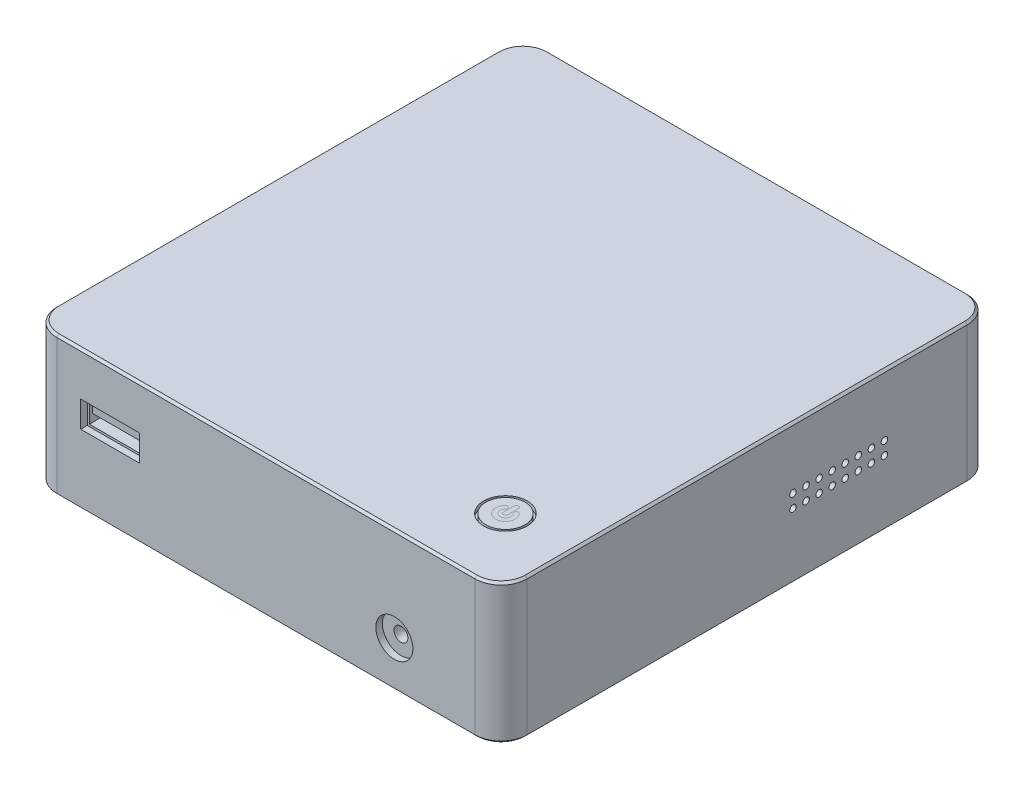
SolidWorks part; units mm, degrees
ref_plane "前视基准面" through (0, 0, 0) normal (0, 0, 1) x (1, 0, 0)
ref_plane "上视基准面" through (0, 0, 0) normal (0, 1, 0) x (1, 0, 0)
ref_plane "右视基准面" through (0, 0, 0) normal (1, 0, 0) x (0, 0, -1)
sketch "草图1" plane through (0, 0, 0) normal (0, 1, 0) x (1, 0, 0)
  line L1 (-48, -56.5) -> (48, -56.5)
  line L2 (-54, -50.5) -> (-54, 50.5)
  line L3 (-48, 56.5) -> (48, 56.5)
  line L4 (54, -50.5) -> (54, 50.5)
  line L5 (-54, -56.5) -> (54, 56.5) construction
  line L6 (-54, 56.5) -> (54, -56.5) construction
  arc A0 (-54, -50.5) -> (-48, -56.5) centre (-48, -50.5) ccw
  arc A1 (48, -56.5) -> (54, -50.5) centre (48, -50.5) ccw
  arc A2 (48, 56.5) -> (54, 50.5) centre (48, 50.5) cw
  arc A3 (-54, 50.5) -> (-48, 56.5) centre (-48, 50.5) cw
  point P0 (0, 0)
  dimension "D3" = 6
  dimension "D1" = 113
  dimension "D2" = 108
extrude "凸台-拉伸1" add sketch "草图1" along normal blind 32
sketch "草图2" plane through (0, 32, 0) normal (0, 1, 0) x (1, 0, 0)
  line L0 (54, -50.5) -> (54, 50.5) construction
  line L1 (-48, -56.5) -> (48, -56.5) construction
  circle A0 centre (39, -40.5) radius 5
  circle A1 centre (39, -40.5) radius 4.5
  dimension "D1" = 15
  dimension "D2" = 10
  dimension "D3" = 16
  dimension "D4" = 0.5
extrude "切除-拉伸1" cut sketch "草图2" against normal blind 1
sketch "草图3" plane through (0, 32, 0) normal (0, 1, 0) x (1, 0, 0)
  line L0 (39, -38) -> (39, -40.5) construction
  line L1 (39.5, -38) -> (39.5, -40.5)
  line L2 (38.5, -38) -> (38.5, -40.5)
  line L3 (39, -40.5) -> (39, -42.25) construction
  arc A0 (39.5, -38) -> (38.5, -38) centre (39, -38) ccw
  arc A1 (38.5, -40.5) -> (39.5, -40.5) centre (39, -40.5) ccw
  arc A2 (37.7626, -39.2626) -> (40.2374, -39.2626) centre (39, -40.5) ccw construction
  arc A3 (37.409, -38.909) -> (40.591, -38.909) centre (39, -40.5) ccw
  arc A4 (38.1161, -39.6161) -> (39.8839, -39.6161) centre (39, -40.5) ccw
  arc A5 (38.1161, -39.6161) -> (37.409, -38.909) centre (37.7626, -39.2626) ccw
  arc A6 (40.591, -38.909) -> (39.8839, -39.6161) centre (40.2374, -39.2626) ccw
  point P2 (39, -39.25)
  point P11 (39, -42.25)
  point P16 (39, -40.5)
  point P17 (40.4505, -39.521)
  dimension "D1" = 0.5
  dimension "D2" = 0.5
  dimension "D3" = 1.75
  dimension "D4" = 2.5
  dimension "D5" = 90
split line "分割线1"
sketch "草图4" plane through (54, 0, 0) normal (1, 0, 0) x (0, 0, -1)
  line L0 (56.5, 32) -> (56.5, 0) construction
  line L1 (-50.5, 0) -> (50.5, 0) construction
  circle A0 centre (10.5, 18) radius 0.75
  circle A1 centre (13.5, 18) radius 0.75
  circle A2 centre (16.5, 18) radius 0.75
  circle A3 centre (19.5, 18) radius 0.75
  circle A4 centre (22.5, 18) radius 0.75
  circle A5 centre (25.5, 18) radius 0.75
  circle A6 centre (28.5, 18) radius 0.75
  circle A7 centre (31.5, 18) radius 0.75
  circle A8 centre (13.5, 15) radius 0.75
  circle A9 centre (16.5, 15) radius 0.75
  circle A10 centre (19.5, 15) radius 0.75
  circle A11 centre (22.5, 15) radius 0.75
  circle A12 centre (25.5, 15) radius 0.75
  circle A13 centre (28.5, 15) radius 0.75
  circle A14 centre (31.5, 15) radius 0.75
  circle A15 centre (10.5, 15) radius 0.75
  point P2 (-8.9295, 21.1833)
  point P4 (0, 0)
  point P34 (0, 0)
  point P35 (3.3735, 19.2577)
  dimension "D4" = 1.5
  dimension "D5" = 3
  dimension "D6" = 25
  dimension "D7" = 15
  dimension "D3" = 3
  dimension "D1" = 8
  dimension "D2" = 2
extrude "切除-拉伸2" cut sketch "草图4" against normal blind 3
sketch "草图5" plane through (0, 0, 56.5) normal (0, 0, 1) x (1, 0, 0)
  line L0 (-48, 0) -> (48, 0) construction
  line L1 (-42.5, 22) -> (-29, 22)
  line L2 (-42.5, 22) -> (-42.5, 16)
  line L3 (-42.5, 16) -> (-29, 16)
  line L4 (-29, 22) -> (-29, 16)
  line L5 (54, 32) -> (54, 0) construction
  line L6 (-48, 32) -> (48, 32) construction
  line L7 (-54, 32) -> (-54, 0) construction
  circle A0 centre (29.5, 10.5) radius 4.25
  dimension "D1" = 8.5
  dimension "D2" = 10.5
  dimension "D3" = 24.5
  dimension "D4" = 13.5
  dimension "D5" = 6
  dimension "D6" = 10
  dimension "D7" = 11.5
extrude "切除-拉伸3" cut sketch "草图5" against normal blind 1.5
sketch "草图6" plane through (0, 0, 55) normal (0, 0, 1) x (1, 0, 0)
  line L0 (-29, 16) -> (-29, 22) construction
  line L1 (-42, 21.5) -> (-29.5, 21.5)
  line L2 (-42, 21.5) -> (-42, 16.5)
  line L3 (-42, 16.5) -> (-29.5, 16.5)
  line L4 (-29.5, 21.5) -> (-29.5, 16.5)
  line L5 (-41.25, 21) -> (-30.25, 21)
  line L6 (-41.25, 21) -> (-41.25, 19)
  line L7 (-41.25, 19) -> (-30.25, 19)
  line L8 (-30.25, 21) -> (-30.25, 19)
  line L9 (-29, 22) -> (-42.5, 22) construction
  circle A0 centre (29.5, 10.5) radius 1.6
  point P11 (-29.5, 19)
  point P14 (-29, 19)
  point P15 (-35.75, 21.5)
  point P18 (-35.75, 22)
  point P19 (-35.75, 21)
  dimension "D1" = 3.2
  dimension "D2" = 5
  dimension "D3" = 12.5
  dimension "D4" = 11
  dimension "D5" = 2
  dimension "D6" = 0.5
extrude "切除-拉伸4" cut sketch "草图6" against normal blind 10
sketch "草图7" plane through (-54, 0, 0) normal (-1, 0, 0) x (0, 0, 1)
  line L0 (56.5, 32) -> (56.5, 0) construction
  line L1 (-3.5, 22) -> (10, 22)
  line L2 (-3.5, 22) -> (-3.5, 16)
  line L3 (-3.5, 16) -> (10, 16)
  line L4 (10, 22) -> (10, 16)
  line L5 (19, 22) -> (32.5, 22)
  line L6 (19, 22) -> (19, 16)
  line L7 (19, 16) -> (32.5, 16)
  line L8 (32.5, 22) -> (32.5, 16)
  line L9 (-50.5, 32) -> (50.5, 32) construction
  dimension "D1" = 6
  dimension "D2" = 13.5
  dimension "D3" = 9
  dimension "D4" = 24
  dimension "D5" = 10
extrude "切除-拉伸5" cut sketch "草图7" against normal blind 1.5
sketch "草图8" plane through (-52.5, 0, 0) normal (-1, 0, 0) x (0, 0, 1)
  line L0 (10, 22) -> (-3.5, 22) construction
  line L5 (-2.25, 21) -> (8.75, 21)
  line L6 (-2.25, 21) -> (-2.25, 19)
  line L7 (-2.25, 19) -> (8.75, 19)
  line L8 (8.75, 21) -> (8.75, 19)
  line L13 (20.25, 21) -> (31.25, 21)
  line L14 (20.25, 21) -> (20.25, 19)
  line L15 (20.25, 19) -> (31.25, 19)
  line L16 (31.25, 21) -> (31.25, 19)
  line L23 (9.5, 16.5) -> (9.5, 21.5)
  line L24 (-3, 16.5) -> (9.5, 16.5)
  line L25 (-3, 21.5) -> (-3, 16.5)
  line L26 (9.5, 21.5) -> (-3, 21.5)
  line L27 (9.5, 16.5) -> (9.5, 21.5)
  line L28 (-3, 16.5) -> (9.5, 16.5)
  line L29 (-3, 21.5) -> (-3, 16.5)
  line L30 (9.5, 21.5) -> (-3, 21.5)
  line L41 (19.5, 16.5) -> (32, 16.5)
  line L42 (32, 16.5) -> (32, 21.5)
  line L43 (32, 21.5) -> (19.5, 21.5)
  line L44 (19.5, 21.5) -> (19.5, 16.5)
  line L45 (19.5, 16.5) -> (32, 16.5)
  line L46 (32, 16.5) -> (32, 21.5)
  line L47 (32, 21.5) -> (19.5, 21.5)
  line L48 (19.5, 21.5) -> (19.5, 16.5)
  point P0 (25.75, 21)
  point P1 (25.75, 21.5)
  point P18 (3.25, 22)
  point P19 (3.25, 21)
  dimension "D1" = 0.5
  dimension "D3" = 2
  dimension "D4" = 11
  dimension "D5" = 0.5
  dimension "D2" = 0.5
extrude "切除-拉伸6" cut sketch "草图8" against normal blind 10
sketch "草图9" plane through (0, 0, -56.5) normal (0, 0, -1) x (-1, 0, 0)
  line L0 (-27.5, 7) -> (-14.5, 7)
  line L1 (-44.8, 23) -> (-39.8, 23)
  line L2 (-45.8, 22) -> (-45.8, 21)
  line L3 (-44.8, 20) -> (-39.8, 20)
  line L4 (-38.8, 22) -> (-38.8, 21)
  line L5 (-36, 26.5) -> (-9.5, 26.5)
  line L6 (-37, 25.5) -> (-37, 18.7)
  line L7 (-36, 17.7) -> (-9.5, 17.7)
  line L8 (-8.5, 25.5) -> (-8.5, 18.7)
  line L9 (-5.5, 26.5) -> (21, 26.5)
  line L10 (-6.5, 25.5) -> (-6.5, 18.7)
  line L11 (-5.5, 17.7) -> (21, 17.7)
  line L12 (22, 25.5) -> (22, 18.7)
  line L13 (29, 21.7) -> (40.5, 21.7)
  line L14 (28, 20.7) -> (28, 10.2)
  line L15 (31, 7.2) -> (38.5, 7.2)
  line L16 (41.5, 20.7) -> (41.5, 10.2)
  line L17 (-13.5, 8) -> (-13.5, 9.5858)
  line L18 (-13.7929, 10.2929) -> (-15.7071, 12.2071)
  line L19 (-16.4142, 12.5) -> (-25.5858, 12.5)
  line L20 (-26.2929, 12.2071) -> (-28.2071, 10.2929)
  line L21 (-28.5, 9.5858) -> (-28.5, 8)
  line L22 (12.0429, 4.6071) -> (12.4571, 4.1929)
  line L23 (-5, 13.7) -> (1.5, 13.7)
  line L24 (-6, 12.7) -> (-6, 9.2)
  line L25 (-5, 8.2) -> (1.5, 8.2)
  line L26 (2.5, 12.7) -> (2.5, 9.2)
  line L27 (9.5, 14.7) -> (21, 14.7)
  line L28 (8.5, 13.7) -> (8.5, 5.9)
  line L29 (9.5, 4.9) -> (11.3358, 4.9)
  line L30 (22, 13.7) -> (22, 5.9)
  line L31 (13.1642, 3.9) -> (17.3358, 3.9)
  line L32 (18.0429, 4.1929) -> (18.4571, 4.6071)
  line L33 (-48, 0) -> (48, 0) construction
  line L34 (-54, 32) -> (-54, 0) construction
  line L35 (-48, 32) -> (48, 32) construction
  line L36 (54, 32) -> (54, 0) construction
  line L37 (19.1642, 4.9) -> (21, 4.9)
  line L38 (15.25, 3.9) -> (15.25, 14.7) construction
  circle A0 centre (-39, 9.5) radius 5
  arc A1 (28, 10.2) -> (31, 7.2) centre (31, 10.2) ccw
  arc A2 (38.5, 7.2) -> (41.5, 10.2) centre (38.5, 10.2) ccw
  arc A3 (1.5, 8.2) -> (2.5, 9.2) centre (1.5, 9.2) ccw
  arc A4 (1.5, 13.7) -> (2.5, 12.7) centre (1.5, 12.7) cw
  arc A5 (-5, 13.7) -> (-6, 12.7) centre (-5, 12.7) ccw
  arc A6 (-6, 9.2) -> (-5, 8.2) centre (-5, 9.2) ccw
  arc A7 (-27.5, 7) -> (-28.5, 8) centre (-27.5, 8) cw
  arc A8 (-14.5, 7) -> (-13.5, 8) centre (-14.5, 8) ccw
  arc A9 (-13.5, 9.5858) -> (-13.7929, 10.2929) centre (-14.5, 9.5858) ccw
  arc A10 (-15.7071, 12.2071) -> (-16.4142, 12.5) centre (-16.4142, 11.5) ccw
  arc A11 (-25.5858, 12.5) -> (-26.2929, 12.2071) centre (-25.5858, 11.5) ccw
  arc A12 (-28.2071, 10.2929) -> (-28.5, 9.5858) centre (-27.5, 9.5858) ccw
  arc A13 (-39.8, 20) -> (-38.8, 21) centre (-39.8, 21) ccw
  arc A14 (-39.8, 23) -> (-38.8, 22) centre (-39.8, 22) cw
  arc A15 (-45.8, 21) -> (-44.8, 20) centre (-44.8, 21) ccw
  arc A16 (-44.8, 23) -> (-45.8, 22) centre (-44.8, 22) ccw
  arc A17 (-37, 18.7) -> (-36, 17.7) centre (-36, 18.7) ccw
  arc A18 (-36, 26.5) -> (-37, 25.5) centre (-36, 25.5) ccw
  arc A19 (-9.5, 26.5) -> (-8.5, 25.5) centre (-9.5, 25.5) cw
  arc A20 (-9.5, 17.7) -> (-8.5, 18.7) centre (-9.5, 18.7) ccw
  arc A21 (-6.5, 18.7) -> (-5.5, 17.7) centre (-5.5, 18.7) ccw
  arc A22 (-5.5, 26.5) -> (-6.5, 25.5) centre (-5.5, 25.5) ccw
  arc A23 (21, 26.5) -> (22, 25.5) centre (21, 25.5) cw
  arc A24 (21, 17.7) -> (22, 18.7) centre (21, 18.7) ccw
  arc A25 (9.5, 14.7) -> (8.5, 13.7) centre (9.5, 13.7) ccw
  arc A26 (8.5, 5.9) -> (9.5, 4.9) centre (9.5, 5.9) ccw
  arc A27 (12.0429, 4.6071) -> (11.3358, 4.9) centre (11.3358, 3.9) ccw
  arc A28 (12.4571, 4.1929) -> (13.1642, 3.9) centre (13.1642, 4.9) ccw
  arc A29 (17.3358, 3.9) -> (18.0429, 4.1929) centre (17.3358, 4.9) ccw
  arc A30 (18.4571, 4.6071) -> (19.1642, 4.9) centre (19.1642, 3.9) cw
  arc A31 (21, 4.9) -> (22, 5.9) centre (21, 5.9) ccw
  arc A32 (21, 14.7) -> (22, 13.7) centre (21, 13.7) cw
  arc A33 (40.5, 21.7) -> (41.5, 20.7) centre (40.5, 20.7) cw
  arc A34 (29, 21.7) -> (28, 20.7) centre (29, 20.7) ccw
  point P40 (-21, 12.5)
  point P41 (-21, 7)
  point P49 (18.0875, 2.4436)
  point P50 (20.0821, 4.9)
  point P57 (2.5, 8.2)
  point P60 (2.5, 13.7)
  point P63 (-6, 13.7)
  point P68 (-28.5, 7)
  point P71 (-13.5, 7)
  point P74 (-13.5, 10)
  point P77 (-16, 12.5)
  point P84 (-38.8, 20)
  point P87 (-38.8, 23)
  point P92 (-45.8, 23)
  point P95 (-37, 17.7)
  point P98 (-37, 26.5)
  point P101 (-8.5, 26.5)
  point P114 (8.5, 14.7)
  point P119 (11.75, 4.9)
  point P126 (18.75, 4.9)
  point P129 (22, 4.9)
  point P132 (22, 14.7)
  point P135 (41.5, 21.7)
  point P138 (28, 21.7)
  dimension "D1" = 10
  dimension "D2" = 9.5
  dimension "D3" = 15
  dimension "D33" = 3
  dimension "D34" = 1
  dimension "D4" = 5.5
  dimension "D5" = 7
  dimension "D6" = 15
  dimension "D7" = 45
  dimension "D8" = 2.5
  dimension "D9" = 10.5
  dimension "D10" = 5.5
  dimension "D11" = 2
  dimension "D12" = 28.5
  dimension "D13" = 8.8
  dimension "D14" = 17
  dimension "D15" = 1.8
  dimension "D16" = 7
  dimension "D17" = 3
  dimension "D18" = 9
  dimension "D19" = 12.5
  dimension "D20" = 14.5
  dimension "D21" = 10.3
  dimension "D22" = 13.5
  dimension "D23" = 6
  dimension "D24" = 13.5
  dimension "D25" = 3
  dimension "D26" = 9.8
  dimension "D27" = 7
  dimension "D28" = 1
  dimension "D29" = 6
  dimension "D30" = 8.5
  dimension "D31" = 5.5
  dimension "D32" = 4
extrude "切除-拉伸7" cut sketch "草图9" against normal blind 1.5
sketch "草图10" plane through (0, 0, -55) normal (0, 0, -1) x (-1, 0, 0)
  line L4 (-38.8, 21) -> (-38.8, 22)
  line L5 (-39.8, 23) -> (-44.8, 23)
  line L6 (-45.8, 22) -> (-45.8, 21)
  line L7 (-44.8, 20) -> (-39.8, 20)
  line L8 (-38.8, 21) -> (-38.8, 22)
  line L9 (-39.8, 23) -> (-44.8, 23)
  line L10 (-45.8, 22) -> (-45.8, 21)
  line L11 (-44.8, 20) -> (-39.8, 20)
  line L20 (-27.5, 7.5) -> (-14.5, 7.5)
  line L21 (-14, 8) -> (-14, 9.5858)
  line L22 (-14.1464, 9.9393) -> (-16.0607, 11.8536)
  line L23 (-16.4142, 12) -> (-25.5858, 12)
  line L24 (-25.9393, 11.8536) -> (-27.8536, 9.9393)
  line L25 (-28, 9.5858) -> (-28, 8)
  line L26 (-27.5, 7.5) -> (-14.5, 7.5)
  line L27 (-14, 8) -> (-14, 9.5858)
  line L28 (-14.1464, 9.9393) -> (-16.0607, 11.8536)
  line L29 (-16.4142, 12) -> (-25.5858, 12)
  line L30 (-25.9393, 11.8536) -> (-27.8536, 9.9393)
  line L31 (-28, 9.5858) -> (-28, 8)
  line L34 (21, 14.7) -> (9.5, 14.7) construction
  line L35 (10, 14.2) -> (20.5, 14.2)
  line L36 (9.5, 13.7) -> (9.5, 6.7)
  line L37 (10, 6.2) -> (13.25, 6.2)
  line L38 (2, 9.2) -> (2, 12.7)
  line L39 (1.5, 13.2) -> (-5, 13.2)
  line L40 (-5.5, 12.7) -> (-5.5, 9.2)
  line L41 (-5, 8.7) -> (1.5, 8.7)
  line L42 (2, 9.2) -> (2, 12.7)
  line L43 (1.5, 13.2) -> (-5, 13.2)
  line L44 (-5.5, 12.7) -> (-5.5, 9.2)
  line L45 (-5, 8.7) -> (1.5, 8.7)
  line L46 (21, 13.7) -> (21, 6.7)
  line L47 (21, 14.7) -> (9.5, 14.7) construction
  line L48 (22, 5.9) -> (22, 13.7) construction
  line L49 (13.1642, 3.9) -> (17.3358, 3.9) construction
  line L50 (31.75, 11.7) -> (37.75, 11.7) construction
  line L51 (13.25, 6.2) -> (13.25, 3.9)
  line L52 (13.25, 3.9) -> (17.25, 3.9)
  line L53 (17.25, 6.2) -> (17.25, 3.9)
  line L54 (17.25, 6.2) -> (20.5, 6.2)
  line L55 (29, 20.7) -> (40.5, 20.7)
  line L56 (28.5, 20.2) -> (28.5, 16.2)
  line L57 (29, 15.7) -> (40.5, 15.7)
  line L58 (41, 20.2) -> (41, 16.2)
  line L59 (29.75, 20.2) -> (39.75, 20.2)
  line L60 (29.25, 19.7) -> (29.25, 18.7)
  line L61 (29.75, 18.2) -> (39.75, 18.2)
  line L62 (40.25, 19.7) -> (40.25, 18.7)
  line L63 (31.75, 13.2) -> (37.75, 13.2)
  line L64 (31.75, 10.2) -> (37.75, 10.2)
  line L65 (31.75, 11.7) -> (37.75, 11.7) construction
  line L66 (31.75, 11.95) -> (37.75, 11.95)
  line L67 (31.75, 11.45) -> (37.75, 11.45)
  line L68 (31, 7.2) -> (38.5, 7.2) construction
  line L69 (40.5, 21.7) -> (29, 21.7) construction
  line L71 (40.5, 21.7) -> (29, 21.7) construction
  line L72 (-25.5, 9.5858) -> (-16.5, 9.5858) construction
  line L73 (-25.5, 9.8358) -> (-16.5, 9.8358)
  line L74 (-25.5, 9.3358) -> (-16.5, 9.3358)
  line L76 (-5.25, 11.95) -> (1.75, 11.95)
  line L77 (-5.25, 11.95) -> (-5.25, 9.95)
  line L78 (-5.25, 9.95) -> (1.75, 9.95)
  line L79 (1.75, 11.95) -> (1.75, 9.95)
  circle A0 centre (-39, 9.5) radius 3.25
  circle A1 centre (-39, 9.5) radius 1.25
  arc A4 (-39.8, 20) -> (-38.8, 21) centre (-39.8, 21) ccw
  arc A5 (-38.8, 22) -> (-39.8, 23) centre (-39.8, 22) ccw
  arc A6 (-44.8, 23) -> (-45.8, 22) centre (-44.8, 22) ccw
  arc A7 (-45.8, 21) -> (-44.8, 20) centre (-44.8, 21) ccw
  arc A8 (-39.8, 20) -> (-38.8, 21) centre (-39.8, 21) ccw
  arc A9 (-38.8, 22) -> (-39.8, 23) centre (-39.8, 22) ccw
  arc A10 (-44.8, 23) -> (-45.8, 22) centre (-44.8, 22) ccw
  arc A11 (-45.8, 21) -> (-44.8, 20) centre (-44.8, 21) ccw
  arc A22 (-28, 8) -> (-27.5, 7.5) centre (-27.5, 8) ccw
  arc A23 (-14.5, 7.5) -> (-14, 8) centre (-14.5, 8) ccw
  arc A24 (-14, 9.5858) -> (-14.1464, 9.9393) centre (-14.5, 9.5858) ccw
  arc A25 (-16.0607, 11.8536) -> (-16.4142, 12) centre (-16.4142, 11.5) ccw
  arc A26 (-25.5858, 12) -> (-25.9393, 11.8536) centre (-25.5858, 11.5) ccw
  arc A27 (-27.8536, 9.9393) -> (-28, 9.5858) centre (-27.5, 9.5858) ccw
  arc A28 (-28, 8) -> (-27.5, 7.5) centre (-27.5, 8) ccw
  arc A29 (-14.5, 7.5) -> (-14, 8) centre (-14.5, 8) ccw
  arc A30 (-14, 9.5858) -> (-14.1464, 9.9393) centre (-14.5, 9.5858) ccw
  arc A31 (-16.0607, 11.8536) -> (-16.4142, 12) centre (-16.4142, 11.5) ccw
  arc A32 (-25.5858, 12) -> (-25.9393, 11.8536) centre (-25.5858, 11.5) ccw
  arc A33 (-27.8536, 9.9393) -> (-28, 9.5858) centre (-27.5, 9.5858) ccw
  arc A36 (31.75, 13.2) -> (31.75, 10.2) centre (31.75, 11.7) ccw
  arc A37 (37.75, 10.2) -> (37.75, 13.2) centre (37.75, 11.7) ccw
  arc A38 (31.75, 11.95) -> (31.75, 11.45) centre (31.75, 11.7) ccw
  arc A39 (37.75, 11.45) -> (37.75, 11.95) centre (37.75, 11.7) ccw
  arc A40 (1.5, 8.7) -> (2, 9.2) centre (1.5, 9.2) ccw
  arc A41 (2, 12.7) -> (1.5, 13.2) centre (1.5, 12.7) ccw
  arc A42 (-5, 13.2) -> (-5.5, 12.7) centre (-5, 12.7) ccw
  arc A43 (-5.5, 9.2) -> (-5, 8.7) centre (-5, 9.2) ccw
  arc A44 (1.5, 8.7) -> (2, 9.2) centre (1.5, 9.2) ccw
  arc A45 (2, 12.7) -> (1.5, 13.2) centre (1.5, 12.7) ccw
  arc A46 (-5, 13.2) -> (-5.5, 12.7) centre (-5, 12.7) ccw
  arc A47 (-5.5, 9.2) -> (-5, 8.7) centre (-5, 9.2) ccw
  arc A48 (10, 14.2) -> (9.5, 13.7) centre (10, 13.7) ccw
  arc A49 (9.5, 6.7) -> (10, 6.2) centre (10, 6.7) ccw
  arc A50 (20.5, 6.2) -> (21, 6.7) centre (20.5, 6.7) ccw
  arc A51 (20.5, 14.2) -> (21, 13.7) centre (20.5, 13.7) cw
  arc A52 (39.75, 20.2) -> (40.25, 19.7) centre (39.75, 19.7) cw
  arc A53 (39.75, 18.2) -> (40.25, 18.7) centre (39.75, 18.7) ccw
  arc A54 (29.25, 18.7) -> (29.75, 18.2) centre (29.75, 18.7) ccw
  arc A55 (29.75, 20.2) -> (29.25, 19.7) centre (29.75, 19.7) ccw
  arc A56 (29, 20.7) -> (28.5, 20.2) centre (29, 20.2) ccw
  arc A57 (28.5, 16.2) -> (29, 15.7) centre (29, 16.2) ccw
  arc A58 (40.5, 15.7) -> (41, 16.2) centre (40.5, 16.2) ccw
  arc A59 (40.5, 20.7) -> (41, 20.2) centre (40.5, 20.2) cw
  arc A60 (-25.5, 9.8358) -> (-25.5, 9.3358) centre (-25.5, 9.5858) ccw
  arc A61 (-16.5, 9.3358) -> (-16.5, 9.8358) centre (-16.5, 9.5858) ccw
  point P20 (15.25, 14.2)
  point P23 (15.25, 14.7)
  point P74 (34.75, 11.7)
  point P81 (34.75, 11.7)
  point P86 (-21, 9.5858)
  point P89 (34.75, 7.2)
  point P90 (34.75, 20.7)
  point P91 (34.75, 20.2)
  point P94 (34.75, 21.7)
  point P103 (21, 6.2)
  point P106 (21, 14.2)
  point P109 (40.25, 20.2)
  point P114 (29.25, 18.2)
  point P117 (29.25, 20.2)
  point P120 (28.5, 20.7)
  point P123 (28.5, 15.7)
  point P128 (41, 20.7)
  point P135 (-1.75, 11.95)
  point P136 (-21, 12)
  point P141 (-1.75, 13.2)
  point P142 (1.75, 10.95)
  point P143 (2, 10.95)
  dimension "D2" = 6.5
  dimension "D3" = 2.5
  dimension "D20" = 0.5
  dimension "D6" = 0.5
  dimension "D7" = 1
  dimension "D8" = 8
  dimension "D9" = 4
  dimension "D10" = 3
  dimension "D11" = 0.5
  dimension "D12" = 6
  dimension "D13" = 4.5
  dimension "D14" = 12.5
  dimension "D15" = 11
  dimension "D16" = 2
  dimension "D17" = 0.5
  dimension "D18" = 5
  dimension "D19" = 1
  dimension "D21" = 0.5
  dimension "D22" = 9
  dimension "D23" = 7
  dimension "D24" = 2
  dimension "D1" = 0
  dimension "D4" = 0.5
  dimension "D5" = 0.5
extrude "切除-拉伸8" cut sketch "草图10" against normal blind 10
sketch "草图11" plane through (0, 0, -55) normal (0, 0, -1) x (-1, 0, 0)
  line L0 (-36, 17.7) -> (-9.5, 17.7) construction
  line L1 (-36, 26.5) -> (-35, 26.5)
  line L2 (-36, 26.5) -> (-36, 17.7)
  line L3 (-36, 17.7) -> (-35, 17.7)
  line L4 (-35, 26.5) -> (-35, 17.7)
  line L5 (-34.0385, 26.5) -> (-33.0385, 26.5)
  line L6 (-34.0385, 26.5) -> (-34.0385, 17.7)
  line L7 (-34.0385, 17.7) -> (-33.0385, 17.7)
  line L8 (-33.0385, 26.5) -> (-33.0385, 17.7)
  line L9 (-32.0769, 26.5) -> (-31.0769, 26.5)
  line L10 (-32.0769, 26.5) -> (-32.0769, 17.7)
  line L11 (-32.0769, 17.7) -> (-31.0769, 17.7)
  line L12 (-31.0769, 26.5) -> (-31.0769, 17.7)
  line L13 (-30.1154, 26.5) -> (-29.1154, 26.5)
  line L14 (-30.1154, 26.5) -> (-30.1154, 17.7)
  line L15 (-30.1154, 17.7) -> (-29.1154, 17.7)
  line L16 (-29.1154, 26.5) -> (-29.1154, 17.7)
  line L17 (-28.1538, 26.5) -> (-27.1538, 26.5)
  line L18 (-28.1538, 26.5) -> (-28.1538, 17.7)
  line L19 (-28.1538, 17.7) -> (-27.1538, 17.7)
  line L20 (-27.1538, 26.5) -> (-27.1538, 17.7)
  line L21 (-26.1923, 26.5) -> (-25.1923, 26.5)
  line L22 (-26.1923, 26.5) -> (-26.1923, 17.7)
  line L23 (-26.1923, 17.7) -> (-25.1923, 17.7)
  line L24 (-25.1923, 26.5) -> (-25.1923, 17.7)
  line L25 (-24.2308, 26.5) -> (-23.2308, 26.5)
  line L26 (-24.2308, 26.5) -> (-24.2308, 17.7)
  line L27 (-24.2308, 17.7) -> (-23.2308, 17.7)
  line L28 (-23.2308, 26.5) -> (-23.2308, 17.7)
  line L29 (-22.2692, 26.5) -> (-21.2692, 26.5)
  line L30 (-22.2692, 26.5) -> (-22.2692, 17.7)
  line L31 (-22.2692, 17.7) -> (-21.2692, 17.7)
  line L32 (-21.2692, 26.5) -> (-21.2692, 17.7)
  line L33 (-20.3077, 26.5) -> (-19.3077, 26.5)
  line L34 (-20.3077, 26.5) -> (-20.3077, 17.7)
  line L35 (-20.3077, 17.7) -> (-19.3077, 17.7)
  line L36 (-19.3077, 26.5) -> (-19.3077, 17.7)
  line L37 (-18.3462, 26.5) -> (-17.3462, 26.5)
  line L38 (-18.3462, 26.5) -> (-18.3462, 17.7)
  line L39 (-18.3462, 17.7) -> (-17.3462, 17.7)
  line L40 (-17.3462, 26.5) -> (-17.3462, 17.7)
  line L41 (-16.3846, 26.5) -> (-15.3846, 26.5)
  line L42 (-16.3846, 26.5) -> (-16.3846, 17.7)
  line L43 (-16.3846, 17.7) -> (-15.3846, 17.7)
  line L44 (-15.3846, 26.5) -> (-15.3846, 17.7)
  line L45 (-14.4231, 26.5) -> (-13.4231, 26.5)
  line L46 (-14.4231, 26.5) -> (-14.4231, 17.7)
  line L47 (-14.4231, 17.7) -> (-13.4231, 17.7)
  line L48 (-13.4231, 26.5) -> (-13.4231, 17.7)
  line L49 (-12.4615, 26.5) -> (-11.4615, 26.5)
  line L50 (-12.4615, 26.5) -> (-12.4615, 17.7)
  line L51 (-12.4615, 17.7) -> (-11.4615, 17.7)
  line L52 (-11.4615, 26.5) -> (-11.4615, 17.7)
  line L53 (-10.5, 26.5) -> (-9.5, 26.5)
  line L54 (-10.5, 26.5) -> (-10.5, 17.7)
  line L55 (-10.5, 17.7) -> (-9.5, 17.7)
  line L56 (-9.5, 26.5) -> (-9.5, 17.7)
  line L57 (-9.5, 26.5) -> (-36, 26.5) construction
  line L58 (-9.5, 26.5) -> (-36, 26.5) construction
  line L59 (-5.5, 17.7) -> (21, 17.7) construction
  line L60 (-5.5, 26.5) -> (-4.5, 26.5)
  line L61 (-5.5, 26.5) -> (-5.5, 17.7)
  line L62 (-5.5, 17.7) -> (-4.5, 17.7)
  line L63 (-4.5, 26.5) -> (-4.5, 17.7)
  line L64 (-3.5385, 26.5) -> (-2.5385, 26.5)
  line L65 (-3.5385, 26.5) -> (-3.5385, 17.7)
  line L66 (-3.5385, 17.7) -> (-2.5385, 17.7)
  line L67 (-2.5385, 26.5) -> (-2.5385, 17.7)
  line L68 (-1.5769, 26.5) -> (-0.5769, 26.5)
  line L69 (-1.5769, 26.5) -> (-1.5769, 17.7)
  line L70 (-1.5769, 17.7) -> (-0.5769, 17.7)
  line L71 (-0.5769, 26.5) -> (-0.5769, 17.7)
  line L72 (0.3846, 26.5) -> (1.3846, 26.5)
  line L73 (0.3846, 26.5) -> (0.3846, 17.7)
  line L74 (0.3846, 17.7) -> (1.3846, 17.7)
  line L75 (1.3846, 26.5) -> (1.3846, 17.7)
  line L76 (2.3462, 26.5) -> (3.3462, 26.5)
  line L77 (2.3462, 26.5) -> (2.3462, 17.7)
  line L78 (2.3462, 17.7) -> (3.3462, 17.7)
  line L79 (3.3462, 26.5) -> (3.3462, 17.7)
  line L80 (4.3077, 26.5) -> (5.3077, 26.5)
  line L81 (4.3077, 26.5) -> (4.3077, 17.7)
  line L82 (4.3077, 17.7) -> (5.3077, 17.7)
  line L83 (5.3077, 26.5) -> (5.3077, 17.7)
  line L84 (6.2692, 26.5) -> (7.2692, 26.5)
  line L85 (6.2692, 26.5) -> (6.2692, 17.7)
  line L86 (6.2692, 17.7) -> (7.2692, 17.7)
  line L87 (7.2692, 26.5) -> (7.2692, 17.7)
  line L88 (8.2308, 26.5) -> (9.2308, 26.5)
  line L89 (8.2308, 26.5) -> (8.2308, 17.7)
  line L90 (8.2308, 17.7) -> (9.2308, 17.7)
  line L91 (9.2308, 26.5) -> (9.2308, 17.7)
  line L92 (10.1923, 26.5) -> (11.1923, 26.5)
  line L93 (10.1923, 26.5) -> (10.1923, 17.7)
  line L94 (10.1923, 17.7) -> (11.1923, 17.7)
  line L95 (11.1923, 26.5) -> (11.1923, 17.7)
  line L96 (12.1538, 26.5) -> (13.1538, 26.5)
  line L97 (12.1538, 26.5) -> (12.1538, 17.7)
  line L98 (12.1538, 17.7) -> (13.1538, 17.7)
  line L99 (13.1538, 26.5) -> (13.1538, 17.7)
  line L100 (14.1154, 26.5) -> (15.1154, 26.5)
  line L101 (14.1154, 26.5) -> (14.1154, 17.7)
  line L102 (14.1154, 17.7) -> (15.1154, 17.7)
  line L103 (15.1154, 26.5) -> (15.1154, 17.7)
  line L104 (16.0769, 26.5) -> (17.0769, 26.5)
  line L105 (16.0769, 26.5) -> (16.0769, 17.7)
  line L106 (16.0769, 17.7) -> (17.0769, 17.7)
  line L107 (17.0769, 26.5) -> (17.0769, 17.7)
  line L108 (18.0385, 26.5) -> (19.0385, 26.5)
  line L109 (18.0385, 26.5) -> (18.0385, 17.7)
  line L110 (18.0385, 17.7) -> (19.0385, 17.7)
  line L111 (19.0385, 26.5) -> (19.0385, 17.7)
  line L112 (20, 26.5) -> (21, 26.5)
  line L113 (20, 26.5) -> (20, 17.7)
  line L114 (20, 17.7) -> (21, 17.7)
  line L115 (21, 26.5) -> (21, 17.7)
  line L116 (21, 26.5) -> (-5.5, 26.5) construction
  point P65 (17.4569, 26.5)
  dimension "D1" = 1
  dimension "D3" = 1
  dimension "D2" = 14
  dimension "D4" = 14
extrude "切除-拉伸9" cut sketch "草图11" against normal blind 10
hole_wizard "M3 螺纹孔1" positions "草图12" profile "草图13" tap size "M3" standard "GB"
sketch "草图12" plane through (0, 0, 0) normal (0, -1, 0) x (-1, 0, 0)
  line L0 (0, 40) -> (0, -40) construction
  point P0 (0, 40)
  point P2 (0, -40)
  dimension "D1" = 80
sketch "草图13" plane through (0, 0, -40) normal (1, 0, 0) x (0, 0, -1)
  line L0 (0, 0) -> (0, 8.2511)
  line L1 (0, 8.2511) -> (1.25, 7.5)
  line L2 (1.25, 7.5) -> (1.25, 0)
  line L5 (1.25, 0) -> (0, 0)
  line L10 (0, 8.2511) -> (-1.25, 7.5) construction
  line L11 (0, -6.35) -> (0, 107.95) construction
  dimension "螺纹孔钻头直径" = 2.5
  dimension "螺纹孔钻头深度" = 7.5
  dimension "导头角度" = 118
cosmetic thread "孔螺蚊线1" parameters "D1"=6, "D2"=3
cosmetic thread "孔螺蚊线2" parameters "D1"=6, "D2"=3
sketch "草图14" plane through (0, 0, 0) normal (0, -1, 0) x (1, 0, 0)
  line L1 (46, -48.5) -> (-46, -48.5) construction
  line L2 (46, -48.5) -> (46, 48.5) construction
  line L3 (46, 48.5) -> (-46, 48.5) construction
  line L4 (-46, -48.5) -> (-46, 48.5) construction
  line L5 (46, -48.5) -> (-46, 48.5) construction
  line L6 (46, 48.5) -> (-46, -48.5) construction
  circle A0 centre (-46, -48.5) radius 5.5
  circle A1 centre (-46, 48.5) radius 5.5
  circle A2 centre (46, 48.5) radius 5.5
  circle A3 centre (46, -48.5) radius 5.5
  point P0 (47.1687, 45.4104)
  point P8 (0, 0)
  point P9 (-47.0158, -45.4104)
  dimension "D1" = 11
  dimension "D2" = 92
  dimension "D3" = 97
extrude "凸台-拉伸2" add sketch "草图14" along normal blind 2 draft 10
sketch "草图15" plane through (0, 0, 0) normal (0, -1, 0) x (1, 0, 0)
  line L0 (-13, -17.25) -> (13, -17.25)
  line L1 (13, -17.25) -> (13, 17.25)
  line L2 (13, 17.25) -> (-10, 17.25)
  line L3 (-10, 17.25) -> (-13, 14.25)
  line L4 (-13, 14.25) -> (-13, -17.25)
  line L5 (54, 50.5) -> (54, -50.5) construction
  line L6 (-4, -12.25) -> (-4, 17.25) construction
  line L7 (4, -12.25) -> (4, 17.25) construction
  text T0 "微型主机"
  text T1 "V200-V01"
  point P8 (13, 0)
  point P9 (54, 0)
  point P15 (0, 0)
  point P16 (0, 0)
  point P17 (-4, 17.25)
  dimension "D1" = 34.5
  dimension "D2" = 26
  dimension "D3" = 3
  dimension "D4" = 45
  dimension "D5" = 41
  dimension "D6" = 8
  dimension "D7" = 9
  dimension "D8" = 5
split line "分割线2"
chamfer "倒角1" distance 0.5 angle 45 16 edges at (0, 0, -56.5) (-52.2426, 0, -54.7426) (52.2426, 0, -54.7426) (-54, 0, 0) (54, 0, 0) (-52.2426, 0, 54.7426) (52.2426, 0, 54.7426) (0, 0, 56.5) (0, 32, -56.5) (-52.2426, 32, -54.7426) (52.2426, 32, -54.7426) (-54, 32, 0) (54, 32, 0) (-52.2426, 32, 54.7426) (52.2426, 32, 54.7426) (0, 32, 56.5)
